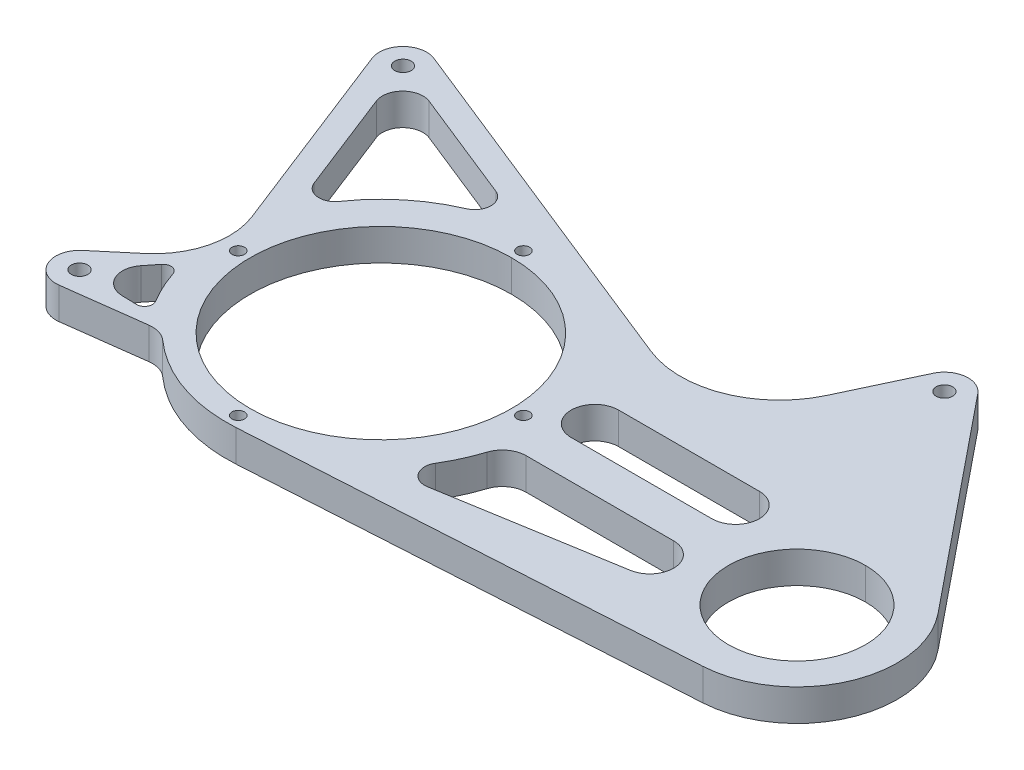
SolidWorks part; units mm, degrees
material "7075-T6 (SN)"
ref_plane "X-Y Datum" through (0, 0, 0) normal (0, 0, 1) x (1, 0, 0)
ref_plane "X-Z Datum" through (0, 0, 0) normal (0, 1, 0) x (1, 0, 0)
ref_plane "Y-Z Datum" through (0, 0, 0) normal (1, 0, 0) x (0, 0, -1)
sketch "Sketch1" plane through (0, 0, 0) normal (0, 1, 0) x (1, 0, 0)
  line L0 (-228.6, -165.1) -> (-123.19, -116.0015) construction
  line L1 (0, 0) -> (54.61, -127) construction
  line L2 (-123.19, -116.0015) -> (54.61, -127) construction
  line L3 (-228.6, -165.1) -> (-228.6, 0) construction
  line L4 (-116.84, 0) -> (0, 0) construction
  line L5 (-228.6, 0) -> (-116.84, 0) construction
  line L10 (-228.6, 0) -> (-123.19, -116.0015) construction
  line L11 (-123.19, -116.0015) -> (10.0337, -23.3342) construction
  line L15 (-207.9749, -9.9568) -> (-62.7807, -68.145)
  line L16 (-119.4523, -177.801) -> (57.0369, -167.1267)
  line L17 (17.4317, -17.3346) -> (85.833, -101.6788)
  line L18 (1.4126, -19.2843) -> (-12.1766, -48.2122)
  line L20 (-211.7072, -147.0868) -> (-198.1514, -135.6819)
  line L21 (-220.3888, -22.2676) -> (-189.4301, -101.4224)
  line L22 (-172.4434, -159.7008) -> (-204.3552, -163.8219)
  circle A0 centre (-211.5182, -18.7982) radius 9.525 construction
  circle A2 centre (10.0337, -23.3342) radius 9.525 construction
  circle A3 centre (-211.5182, -18.7982) radius 3.3 construction
  circle A4 centre (-205.5752, -154.3754) radius 3.3 construction
  circle A5 centre (-123.19, -116.0015) radius 52.3875
  circle A6 centre (54.61, -127) radius 27.5
  circle A7 centre (0, 0) radius 12.7 construction
  circle A8 centre (-228.6, -165.1) radius 12.7 construction
  circle A9 centre (-228.6, 0) radius 12.7 construction
  circle A10 centre (10.0337, -23.3342) radius 3.3 construction
  circle A11 centre (-123.19, -173.1515) radius 2.5 construction
  circle A14 centre (-123.19, -116.0015) radius 61.9125 construction
  circle A15 centre (-123.19, -116.0015) radius 57.15 construction
  circle A17 centre (-205.5752, -154.3754) radius 9.525 construction
  circle A18 centre (54.61, -127) radius 40.2 construction
  circle A19 centre (-48.0406, -31.3647) radius 39.624 construction
  arc A20 (-12.1766, -48.2122) -> (-62.7807, -68.145) centre (-48.0406, -31.3647) cw
  arc A24 (57.0369, -167.1267) -> (85.833, -101.6788) centre (54.61, -127) ccw
  arc A25 (1.4126, -19.2843) -> (17.4317, -17.3346) centre (10.0337, -23.3342) cw
  circle A27 centre (-217.6792, -112.471) radius 30.3329 construction
  arc A29 (-198.1514, -135.6819) -> (-189.4301, -101.4224) centre (-217.6792, -112.471) ccw
  arc A30 (-220.3888, -22.2676) -> (-207.9749, -9.9568) centre (-211.5182, -18.7982) cw
  arc A31 (-164.4265, -162.1827) -> (-119.4523, -177.801) centre (-123.19, -116.0015) ccw
  circle A32 centre (-171.1504, -169.7128) radius 10.0952 construction
  arc A33 (-204.3552, -163.8219) -> (-211.7072, -147.0868) centre (-205.5752, -154.3754) cw
  arc A34 (-172.4434, -159.7008) -> (-164.4265, -162.1827) centre (-171.1504, -169.7128) cw
  point P36 (-123.19, -116.0015)
  dimension "D1" = 165.1
  dimension "D2" = 105.41
  dimension "D8" = 25.4
  dimension "D9" = 104.775
  dimension "D10" = 55
  dimension "D11" = 19.05
  dimension "D12" = 6.6
  dimension "D23" = 5
  dimension "D14" = 123.825
  dimension "D19" = 79.248
  dimension "D20" = 31.3647
  dimension "D16" = 12.7
  dimension "D25" = 20.1904
  dimension "D21" = 20.9
  dimension "D26" = 60.6657
  dimension "D3" = 111.76
  dimension "D4" = 228.6
  dimension "D5" = 127
  dimension "D6" = 49.0985
  dimension "D7" = 283.21
  dimension "D13" = 25.4
  dimension "D15" = 25.4
  dimension "D17" = 25.4
  dimension "D18" = 48.0406
  dimension "D22" = 34.4248
  dimension "D24" = 57.15
  dimension "D27" = 10.9208
extrude "Boss-Extrude1" add sketch "Sketch1" along normal blind 12.7
hole_wizard "M6 Clearance Hole1" positions "Sketch2" profile "Sketch3" hole size "M6" standard "ANSI Metric" end condition through all
sketch "Sketch2" plane through (0, 0, 0) normal (0, -1, 0) x (-1, 0, 0)
  point P0 (-10.0337, -23.3342)
  point P3 (211.5182, -18.7982)
  point P6 (205.5752, -154.3754)
sketch "Sketch3" plane through (10.0337, 0, 23.3342) normal (1, 0, 0) x (0, 0, -1)
  line L0 (0, 0) -> (0, 12.7)
  line L1 (0, 12.7) -> (3.3, 12.7)
  line L2 (3.3, 12.7) -> (3.3, 0)
  line L5 (3.3, 0) -> (0, 0)
  line L11 (0, -6.35) -> (0, 107.95) construction
  dimension "Thru Hole Dia." = 6.6
  dimension "Thru Hole Depth" = 12.7
hole_wizard "Ø5.0mm Dowel Hole1" positions "Sketch4" profile "Sketch5" hole size "Ø5.0" standard "ANSI Metric" end condition through all
sketch "Sketch4" plane through (0, 0, 0) normal (0, -1, 0) x (-1, 0, 0)
  point P0 (123.19, -173.1515)
sketch "Sketch5" plane through (-123.19, 0, 173.1515) normal (1, 0, 0) x (0, 0, -1)
  line L0 (0, 0) -> (0, 12.7)
  line L1 (0, 12.7) -> (2.5, 12.7)
  line L2 (2.5, 12.7) -> (2.5, 0)
  line L5 (2.5, 0) -> (0, 0)
  line L11 (0, -6.35) -> (0, 107.95) construction
  dimension "Thru Hole Dia." = 5
  dimension "Thru Hole Depth" = 12.7
pattern_circular "CirPattern1" count 4 over 360 about axis through (-123.19, 0, 116.0015) along (0, 1, 0) of "Ø5.0mm Dowel Hole1"
ref_point "Point1"
ref_point "Point2"
ref_plane "Plane1" through (-123.19, 0, 0) normal (1, 0, 0) x (0, 0, -1)
ref_plane "Plane2" through (54.61, 0, 0) normal (1, 0, 0) x (0, 0, -1)
split line "Split Line1"
split line "Split Line2"
sketch "Sketch6" plane through (0, 0, 0) normal (0, -1, 0) x (1, 0, 0)
  line L0 (-14.2347, 76.5807) -> (2.0865, 40.7709)
  line L1 (21.6652, 38.5626) -> (49.7711, 75.3598)
  line L2 (-204.6607, 36.3314) -> (-188.6269, 77.3262)
  line L3 (-194.0427, 25.8017) -> (-149.3861, 43.6983)
  line L5 (-8.4565, 85.5642) -> (44.7247, 85.5642)
  line L8 (-220.3888, 22.2676) -> (-189.4301, 101.4224) construction
  line L9 (17.4317, 17.3346) -> (85.833, 101.6788) construction
  line L10 (1.4126, 19.2843) -> (-12.1766, 48.2122) construction
  line L11 (-207.9749, 9.9568) -> (-62.7807, 68.145) construction
  line L15 (-228.6, 165.1) -> (-123.19, 116.0015) construction
  line L17 (-190.9857, 136.0276) -> (-194.6927, 140.6895)
  line L18 (-182.1426, 155.013) -> (-188.0965, 154.851)
  circle A0 centre (10.0337, 23.3342) radius 3.3 construction
  circle A1 centre (10.0337, 23.3342) radius 3.3 construction
  arc A2 (54.61, 99.5) -> (54.61, 154.5) centre (54.61, 127) ccw construction
  circle A3 centre (-8.4565, 79.2142) radius 6.35 construction
  circle A4 centre (44.7247, 79.2142) radius 6.35 construction
  circle A5 centre (12.5377, 45.5343) radius 11.4855 construction
  arc A6 (2.0865, 40.7709) -> (21.6652, 38.5626) centre (12.5377, 45.5343) ccw
  arc A8 (49.7711, 75.3598) -> (44.7247, 85.5642) centre (44.7247, 79.2142) ccw
  arc A9 (-14.2347, 76.5807) -> (-8.4565, 85.5642) centre (-8.4565, 79.2142) cw
  circle A10 centre (-182.5949, 74.967) radius 6.477 construction
  circle A11 centre (-151.7955, 49.7105) radius 6.477 construction
  circle A14 centre (-197.0734, 33.3639) radius 8.1469 construction
  arc A15 (-204.6607, 36.3314) -> (-194.0427, 25.8017) centre (-197.0734, 33.3639) ccw
  arc A25 (-149.3861, 43.6983) -> (-149.2293, 55.6575) centre (-151.7955, 49.7105) ccw
  circle A26 centre (-123.19, 116.0015) radius 65.7225
  circle A27 centre (-123.19, 116.0015) radius 65.7225 construction
  arc A28 (-149.2293, 55.6575) -> (-177.2657, 78.6482) centre (-123.19, 116.0015) cw
  arc A29 (-188.6269, 77.3262) -> (-177.2657, 78.6482) centre (-182.5949, 74.967) cw
  circle A31 centre (-182.0558, 151.8264) radius 3.1877 construction
  circle A32 centre (-188.4906, 138.0115) radius 3.1877 construction
  circle A33 centre (-187.859, 146.1234) radius 8.7308 construction
  arc A34 (-185.4699, 136.9934) -> (-179.3328, 150.1692) centre (-123.19, 116.0015) cw
  arc A35 (-179.3328, 150.1692) -> (-182.1426, 155.013) centre (-182.0558, 151.8264) ccw
  arc A36 (-185.4699, 136.9934) -> (-190.9857, 136.0276) centre (-188.4906, 138.0115) cw
  arc A37 (-194.6927, 140.6895) -> (-188.0965, 154.851) centre (-187.859, 146.1234) cw
  dimension "D3" = 12.7
  dimension "D4" = 22.2001
  dimension "D5" = 12.954
  dimension "D9" = 6.3754
  dimension "D10" = 7.62
  dimension "D1" = 358.331
  dimension "D2" = 0.66
  dimension "D6" = 55.88
  dimension "D7" = 14.4448
  dimension "D8" = 3.81
  dimension "D11" = 7.62
extrude "Cut-Extrude1" cut sketch "Sketch6" against normal through all contours A29 L2 A15 L3 A25 A28 | A37 L17 A36 A34 A35 L18
sketch "Sketch7" plane through (0, 0, 0) normal (0, -1, 0) x (1, 0, 0)
  line L0 (-48.8157, 114.0965) -> (7.5723, 114.0965)
  line L1 (-48.8157, 95.0465) -> (7.5723, 95.0465)
  line L4 (-60.4801, 159.9806) -> (9.1433, 148.338)
  line L6 (-51.5252, 129.4185) -> (7.5723, 129.4185)
  line L7 (-123.19, 116.0015) -> (54.61, 127) construction
  circle A0 centre (-48.8157, 104.5715) radius 9.525 construction
  circle A3 centre (7.5723, 104.5715) radius 9.525 construction
  arc A4 (-48.8157, 95.0465) -> (-48.8157, 114.0965) centre (-48.8157, 104.5715) cw
  arc A5 (7.5723, 95.0465) -> (7.5723, 114.0965) centre (7.5723, 104.5715) ccw
  circle A12 centre (-51.5252, 138.9435) radius 9.525 construction
  circle A13 centre (7.5723, 138.9435) radius 9.525 construction
  circle A14 centre (-61.5483, 153.5923) radius 6.477 construction
  arc A15 (-60.5967, 136.0394) -> (-67.0782, 150.2201) centre (-123.19, 116.0015) ccw
  arc A16 (-67.0782, 150.2201) -> (-60.4801, 159.9806) centre (-61.5483, 153.5923) cw
  arc A17 (-60.5967, 136.0394) -> (-51.5252, 129.4185) centre (-51.5252, 138.9435) ccw
  arc A18 (7.5723, 129.4185) -> (9.1433, 148.338) centre (7.5723, 138.9435) ccw
  circle A28 centre (-123.19, 116.0015) radius 65.7225
  circle A29 centre (-123.19, 116.0015) radius 65.7225 construction
  dimension "D1" = 19.05
  dimension "D2" = 11.43
  dimension "D5" = 12.954
  dimension "D3" = 14.8249
  dimension "D4" = 56.388
  dimension "D7" = 33.7133
  dimension "D6" = 3.81
extrude "Cut-Extrude2" cut sketch "Sketch7" against normal through all
